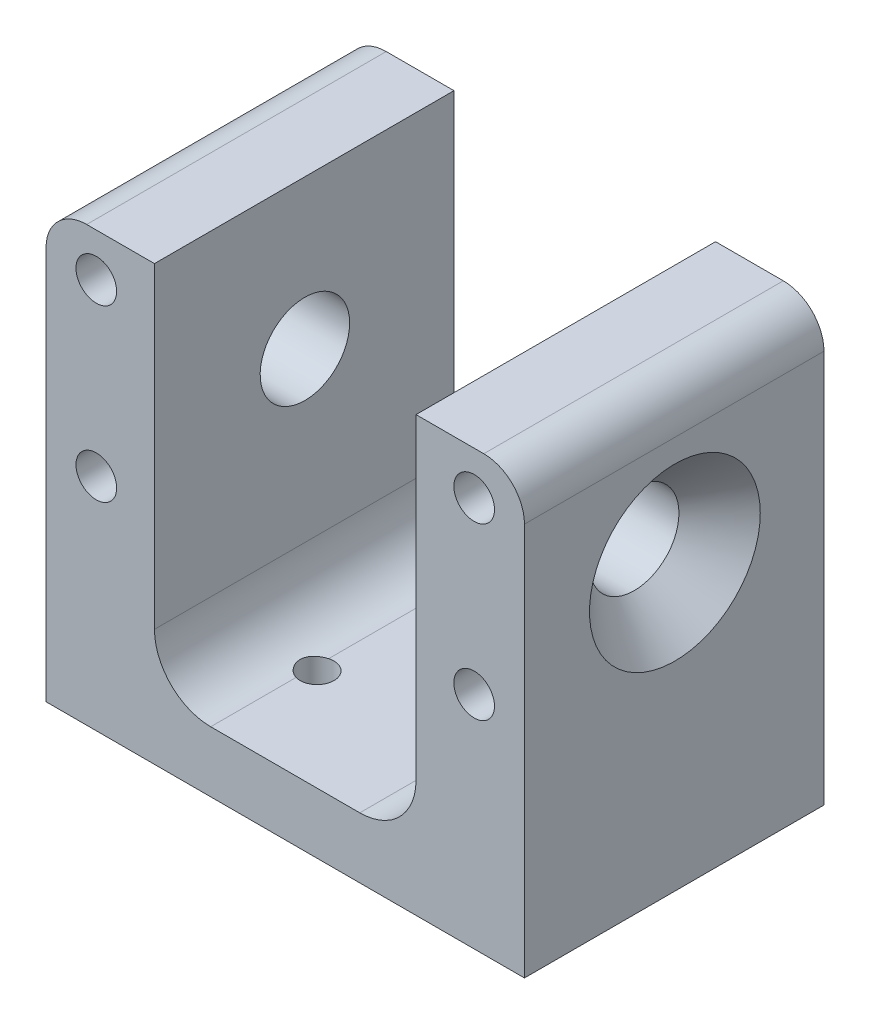
SolidWorks part; units mm, degrees
ref_plane "Front Plane" through (0, 0, 0) normal (0, 0, 1) x (1, 0, 0)
ref_plane "Top Plane" through (0, 0, 0) normal (0, 1, 0) x (1, 0, 0)
ref_plane "Right Plane" through (0, 0, 0) normal (1, 0, 0) x (0, 0, -1)
sketch "Sketch1" plane through (0, 0, 0) normal (0, 1, 0) x (1, 0, 0)
  line L1 (0, 0) -> (35.3, 0)
  line L2 (0, 0) -> (0, 22.1)
  line L3 (0, 22.1) -> (35.3, 22.1)
  line L4 (35.3, 0) -> (35.3, 22.1)
  dimension "D1" = 35.3
  dimension "D2" = 22.1
extrude "Boss-Extrude1" add sketch "Sketch1" along normal blind 32
sketch "Sketch2" plane through (0, 0, 0) normal (0, 0, 1) x (1, 0, 0)
  line L0 (0, 32) -> (35.3, 32) construction
  line L1 (8, 32) -> (27.3, 32)
  line L2 (8, 32) -> (8, 4.48)
  line L3 (8, 4.48) -> (27.3, 4.48)
  line L4 (27.3, 32) -> (27.3, 4.48)
  line L5 (0, 0) -> (35.3, 0) construction
  line L7 (35.3, 32) -> (35.3, 0) construction
  point P7 (17.65, 32)
  point P8 (17.65, 32)
  dimension "D1" = 8
  dimension "D2" = 4.48
extrude "Cut-Extrude1" cut sketch "Sketch2" against normal blind 32
sketch "Sketch3" plane through (0, 0, 0) normal (0, 0, 1) x (1, 0, 0)
  line L0 (8, 8.63) -> (8, 4.48)
  line L1 (8, 32) -> (8, 4.48) construction
  line L2 (8, 4.48) -> (12.15, 4.48)
  line L3 (27.3, 4.48) -> (27.3, 8.63)
  line L4 (27.3, 4.48) -> (27.3, 32) construction
  line L5 (23.15, 4.48) -> (27.3, 4.48)
  line L6 (8, 4.48) -> (27.3, 4.48) construction
  arc A0 (8, 8.63) -> (12.15, 4.48) centre (12.15, 8.63) ccw
  arc A1 (23.15, 4.48) -> (27.3, 8.63) centre (23.15, 8.63) ccw
  dimension "D1" = 11
extrude "Boss-Extrude2" add sketch "Sketch3" against normal up to vertex (22.1 mm away)
fillet "Fillet1" radius 3 2 edges at (35.3, 32, -11.05) (0, 32, -11.05)
sketch "Sketch4" plane through (0, 0, 0) normal (0, 0, 1) x (1, 0, 0)
  line L0 (0, 29) -> (0, 0) construction
  line L1 (3, 32) -> (8, 32) construction
  line L2 (35.3, 29) -> (35.3, 0) construction
  point P0 (3.71, 28.82)
  point P1 (3.71, 16.26)
  point P2 (31.59, 28.82)
  point P3 (31.59, 16.26)
  point P4 (0, 0)
  point P5 (0, 0)
  point P6 (0, 0)
  point P7 (2.9305, 27.5798)
  point P8 (3.7407, 28.255)
  point P9 (7.5894, 13.9406)
  point P10 (4.4159, 14.8184)
  point P11 (4.6185, 15.6286)
  point P16 (29.3311, 28.82)
  dimension "D1" = 12.56
  dimension "D2" = 3.71
  dimension "D3" = 3.18
  dimension "D4" = 3.71
hole_wizard "CSK for M6 Countersunk Flat Head Screw1" positions "Sketch22" profile "Sketch23" countersink size "M6" standard "ISO"
sketch "Sketch22" plane through (35.3, 0, 0) normal (1, 0, 0) x (0, 0, -1)
  line L0 (22.1, 29) -> (22.1, 0) construction
  line L1 (0, 32) -> (22.1, 32) construction
  point P0 (11.1, 21)
  dimension "D1" = 11
  dimension "D2" = 11
sketch "Sketch23" plane through (35.3, 21, -11.1) normal (0, 1, 0) x (0, 0, -1)
  line L0 (0, 0) -> (0, 46.9828)
  line L1 (0, 46.9828) -> (3.3, 45)
  line L2 (3.3, 45) -> (3.3, 3)
  line L3 (3.3, 3) -> (6.3, 0)
  line L5 (6.3, 0) -> (0, 0)
  line L6 (-3.3, 3) -> (-6.3, 0) construction
  line L10 (0, 46.9828) -> (-3.3, 45) construction
  line L11 (0, -6.35) -> (0, 107.95) construction
  dimension "Hole Dia." = 6.6
  dimension "Hole Depth" = 45
  dimension "Near C'Sink Dia." = 12.6
  dimension "Near C'Sink Angle" = 90
  dimension "Drill Angle" = 118
hole_wizard "Ø3.0mm Dowel Hole1" positions "Sketch24" profile "Sketch25" hole size "Ø3.0" standard "ANSI Metric"
sketch "Sketch24" plane through (0, 0, 0) normal (0, 0, 1) x (1, 0, 0)
  point P0 (3.71, 28.82)
  point P3 (3.71, 16.26)
  point P6 (31.59, 28.82)
  point P9 (31.59, 16.26)
sketch "Sketch25" plane through (3.71, 28.82, 0) normal (1, 0, 0) x (0, -1, 0)
  line L0 (0, 0) -> (0, 10.9013)
  line L1 (0, 10.9013) -> (1.5, 10)
  line L2 (1.5, 10) -> (1.5, 0)
  line L5 (1.5, 0) -> (0, 0)
  line L10 (0, 10.9013) -> (-1.5, 10) construction
  line L11 (0, -6.35) -> (0, 107.95) construction
  dimension "Hole Dia." = 3
  dimension "Hole Depth" = 10
  dimension "Drill Angle" = 118
hole_wizard "Ø2.5mm Dowel Hole1" positions "Sketch32" profile "Sketch33" hole size "Ø2.5" standard "ANSI Metric"
sketch "Sketch32" plane through (0, 0, 0) normal (0, -1, 0) x (-1, 0, 0)
  line L0 (0, 0) -> (-35.3, 0) construction
  line L1 (0, 22.1) -> (0, 0) construction
  line L2 (-35.3, 0) -> (-35.3, 22.1) construction
  point P0 (-12.5, 7.5)
  point P2 (-22.8, 7.5)
  dimension "D1" = 7.5
  dimension "D2" = 7.5
  dimension "D3" = 12.5
  dimension "D4" = 12.5
sketch "Sketch33" plane through (12.5, 0, -7.5) normal (1, 0, 0) x (0, 0, -1)
  line L0 (0, 0) -> (0, 10.7511)
  line L1 (0, 10.7511) -> (1.25, 10)
  line L2 (1.25, 10) -> (1.25, 0)
  line L5 (1.25, 0) -> (0, 0)
  line L10 (0, 10.7511) -> (-1.25, 10) construction
  line L11 (0, -6.35) -> (0, 107.95) construction
  dimension "Hole Dia." = 2.5
  dimension "Hole Depth" = 10
  dimension "Drill Angle" = 118
